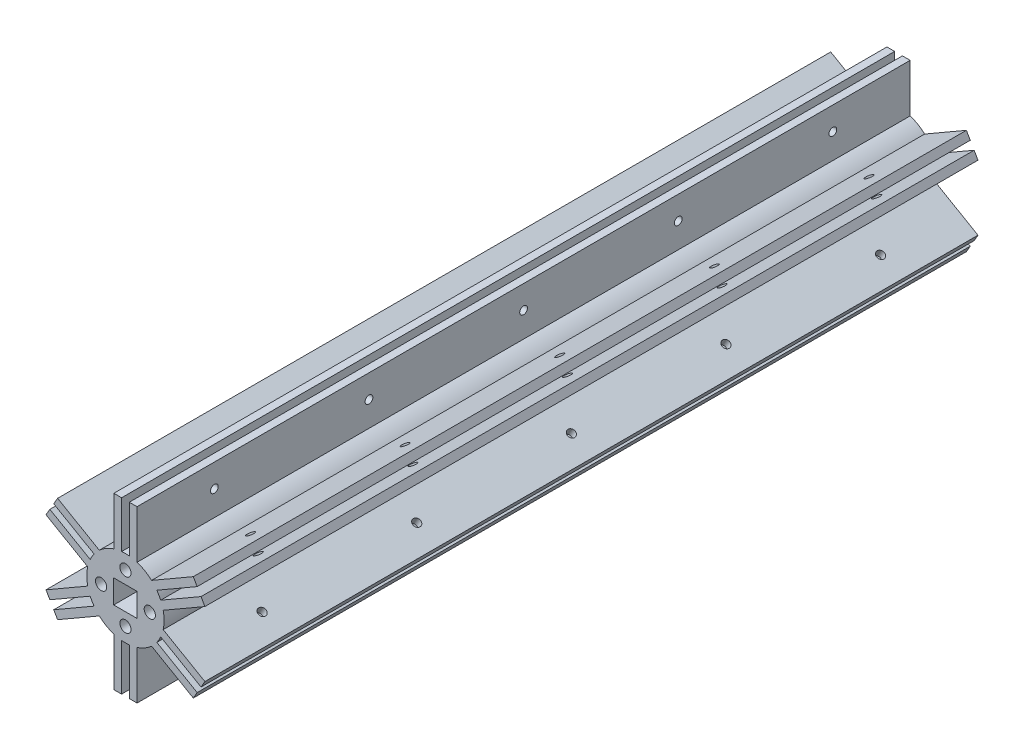
SolidWorks part; units mm, degrees
ref_plane "Front Plane" through (0, 0, 0) normal (0, 0, 1) x (1, 0, 0)
ref_plane "Top Plane" through (0, 0, 0) normal (0, 1, 0) x (1, 0, 0)
ref_plane "Right Plane" through (0, 0, 0) normal (1, 0, 0) x (0, 0, -1)
sketch "Sketch1" plane through (0, 0, 0) normal (0, 0, 1) x (1, 0, 0)
  circle A0 centre (0, 0) radius 10
  dimension "D2" = 20
extrude "Boss-Extrude1" add sketch "Sketch1" along normal mid plane 200
sketch "Sketch4" plane through (0, 0, 100) normal (0, 0, 1) x (1, 0, 0)
  line L0 (18.7973, 0) -> (-18.7973, 0) construction
  line L2 (-3, 0) -> (-1, 0)
  line L3 (0, 0) -> (0, 15.8331) construction
  line L4 (-3, 0) -> (-3, 22)
  line L5 (-3, 22) -> (-1, 22)
  line L6 (-1, 0) -> (-1, 22)
  line L7 (0, -19.8) -> (0, 19.8) construction
  line L8 (3, 22) -> (1, 22)
  line L9 (1, 0) -> (1, 22)
  line L10 (3, 0) -> (1, 0)
  line L11 (3, 0) -> (3, 22)
  dimension "D1" = 22
  dimension "D3" = 1
extrude "Boss-Extrude3" add sketch "Sketch4" against normal up to surface (200 mm away) up to face at (10, 0, -100)
pattern_circular "CirPattern7" count 6 over 360 about axis through (0, 0, 0) along (0, 0, 1) of "Boss-Extrude3"
sketch "Sketch7" plane through (-3, 0, 0) normal (-1, 0, 0) x (0, 0, 1)
  line L0 (-100, 22) -> (100, 22) construction
  line L1 (-100, 9.5394) -> (-100, 22) construction
  circle A0 centre (-80, 16) radius 1
  circle A1 centre (-40, 16) radius 1
  circle A2 centre (0, 16) radius 1
  circle A3 centre (40, 16) radius 1
  circle A4 centre (80, 16) radius 1
  dimension "D1" = 2
  dimension "D2" = 6
  dimension "D3" = 20
  dimension "D4" = 5
extrude "Cut-Extrude2" cut sketch "Sketch7" against normal blind 10
pattern_circular "CirPattern9" count 6 over 360 about axis through (0, 0, 100) along (0, 0, 1) of "Cut-Extrude2"
sketch "Sketch8" plane through (0, 0, 100) normal (0, 0, 1) x (1, 0, 0)
  line L2 (-3.0375, 3.0375) -> (3.0375, 3.0375)
  line L3 (-3.0375, 3.0375) -> (-3.0375, -3.0375)
  line L4 (-3.0375, -3.0375) -> (3.0375, -3.0375)
  line L5 (3.0375, 3.0375) -> (3.0375, -3.0375)
  line L6 (-3.0375, 3.0375) -> (3.0375, -3.0375) construction
  line L7 (-3.0375, -3.0375) -> (3.0375, 3.0375) construction
  point P2 (0, 0)
  point P5 (0, 0)
  point P14 (0, 0)
  point P18 (0, 0)
  dimension "D4" = 6.075
  dimension "D5" = 6.075
extrude "Cut-Extrude3" cut sketch "Sketch8" against normal up to next
sketch "Sketch9" plane through (0, 0, 100) normal (0, 0, 1) x (1, 0, 0)
  line L0 (18.7973, 0) -> (-18.7973, 0) construction
  circle A0 centre (6.3, 0) radius 1.45
  circle A1 centre (0, -6.3) radius 1.45
  circle A2 centre (-6.3, 0) radius 1.45
  circle A3 centre (0, 6.3) radius 1.45
  point P14 (0, 0)
  dimension "D1" = 2.9
  dimension "D2" = 6.3
  dimension "D3" = 4
extrude "Cut-Extrude4" cut sketch "Sketch9" against normal blind 10
equation "\"drumDiameter\" = 20mm"
equation "\"D2@Sketch1\"=\"drumDiameter\""
equation "\"drumLength\"= 200mm"
equation "\"D1@Sketch4\"=\"drumDiameter\"*(0.5+\"drumAbove\")"
equation "\"foamThickness\" = 2"
equation "\"D3@Sketch4\"=\"foamThickness\"/2"
equation "\"drumAbove\"= 0.6"
equation "\"D2@Sketch7\"=\"drumDiameter\"*\"drumAbove\"/2"
equation "\"holderThicc\"= 2"
equation "\"D2@Sketch4\"=\"holderThicc\""
equation "\"D5@Sketch8\"=12.15/2"
